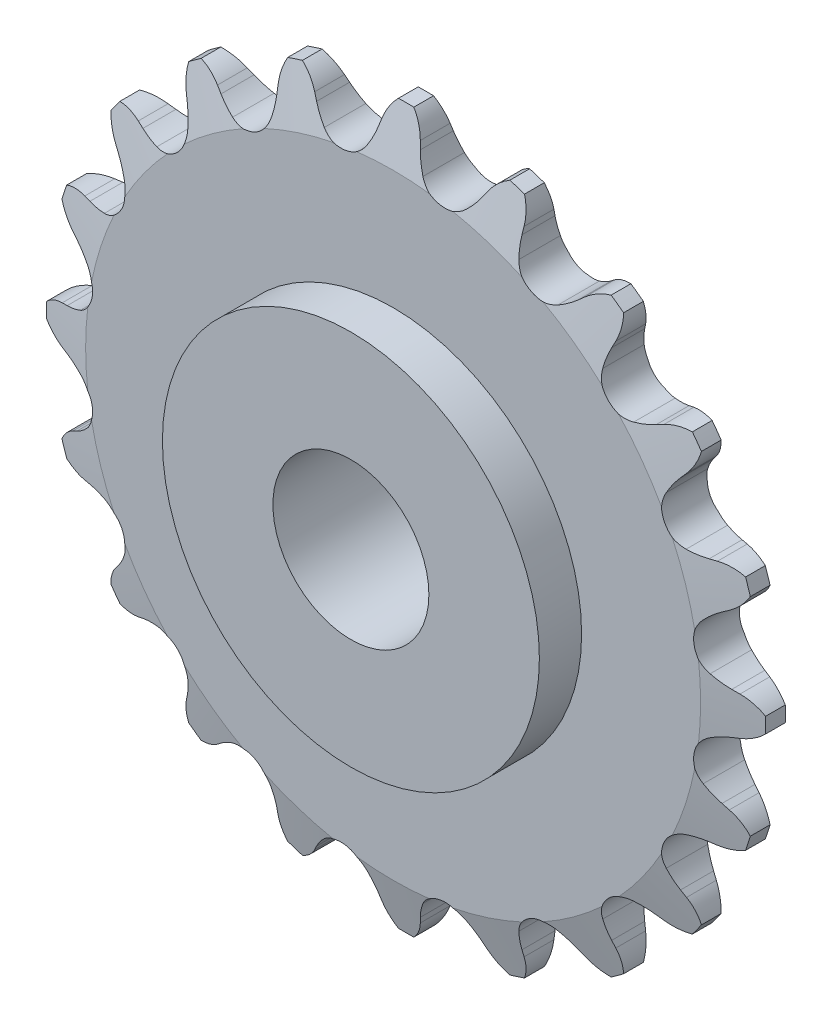
SolidWorks part; units mm, degrees
material "Plain Carbon Steel"
ref_plane "Front Plane" through (0, 0, 0) normal (0, 0, 1) x (1, 0, 0)
ref_plane "Top Plane" through (0, 0, 0) normal (0, 1, 0) x (1, 0, 0)
ref_plane "Right Plane" through (0, 0, 0) normal (1, 0, 0) x (0, 0, -1)
sketch "Sketch0" plane through (0, 0, 0) normal (0, 0, 1) x (1, 0, 0)
  line L0 (3.175, -20.0462) -> (0, 0) construction
  line L1 (0, 0) -> (9.2142, -18.0839) construction
  line L2 (0, 0) -> (-3.175, -20.0462) construction
  line L3 (3.175, -20.0462) -> (9.2142, -18.0839) construction
  line L4 (3.175, -20.0462) -> (-3.175, -20.0462) construction
  line L5 (5.2772, -20.0402) -> (5.0611, -19.6917)
  line L6 (3.175, -20.0462) -> (0, -20.549) construction
  line L7 (1.1739, -20.6901) -> (1.2717, -20.2918)
  line L8 (0, -20.0462) -> (0, -21.9512) construction
  line L9 (4.3326, -18.8048) -> (1.3734, -21.9781) construction
  line L10 (0, 0) -> (0, -20.0462) construction
  line L11 (5.0611, -19.6917) -> (1.3734, -21.9781) construction
  line L12 (0, -21.9512) -> (0, -22.3247) construction
  line L13 (7.5715, -18.6176) -> (5.2772, -20.0402) construction
  circle A0 centre (0, 0) radius 21.9512 construction
  circle A1 centre (0, 0) radius 20.296 construction
  arc A2 (-1.6423, -22.7387) -> (8.5885, -21.1183) centre (0, 0) ccw
  circle A3 centre (0, 0) radius 22.3247 construction
  circle A4 centre (3.175, -20.0462) radius 1.651 construction
  arc A7 (4.3326, -18.8048) -> (1.6905, -19.2233) centre (3.175, -20.0462) ccw
  circle A8 centre (3.175, -20.0462) radius 1.6974 construction
  arc A9 (5.2772, -20.0402) -> (8.5885, -21.1183) centre (7.5715, -18.6176) ccw
  arc A10 (5.0611, -19.6917) -> (4.3326, -18.8048) centre (1.3734, -21.9781) ccw
  arc A11 (1.1739, -20.6901) -> (-1.6423, -22.7387) centre (-1.4478, -20.0462) cw
  arc A12 (1.2717, -20.2918) -> (1.6905, -19.2233) centre (5.4854, -21.3268) cw
  dimension "D1" = 1.6974
  dimension "R" = 1.6974
sketch "Sketch1" plane through (0, 0, 0) normal (1, 0, 0) x (0, 0, -1)
  line L0 (-1.397, 0) -> (1.397, 0)
  line L1 (-1.397, 0) -> (-1.397, 18.7762)
  line L2 (-1.397, 18.7762) -> (-0.6032, 21.9512)
  line L3 (-0.6032, 21.9512) -> (0.6032, 21.9512)
  line L4 (0.6032, 21.9512) -> (1.397, 18.7762)
  line L5 (1.397, 18.7762) -> (1.397, 0)
  line L7 (0, 21.9512) -> (0, 0) construction
  line L8 (-1.397, 18.7762) -> (1.397, 18.7762) construction
  line L9 (0, 21.9512) -> (0, -21.9512) construction
  line L10 (-1.397, 18.7762) -> (-1.397, 21.9512) construction
  line L11 (-1.397, 21.9512) -> (-0.6032, 21.9512) construction
  line L12 (0.6032, 21.9512) -> (1.397, 21.9512) construction
  line L13 (1.397, 21.9512) -> (1.397, 18.7762) construction
revolve "Revolve1" add sketch "Sketch1" angle 360 mid plane about L0
extrude "Cut-Extrude1" cut sketch "Sketch0" against normal through all and the other way through all
pattern_circular "CirPattern1" count 20 over 360 about axis through (0, 0, 0) along (0, 0, 1) of "Cut-Extrude1"
sketch "Sketch2" plane through (0, 0, 0) normal (0, 0, 1) x (1, 0, 0)
  circle A0 centre (0, 0) radius 4.7625 construction
  circle A1 centre (0, 0) radius 11.5094
  circle A2 centre (0, 0) radius 21.971 construction
  dimension "Bore" = 9.525
  dimension "Hub Dia." = 23.0188
  dimension "OD" = 43.942
extrude "Boss-Extrude1" add sketch "Sketch2" along normal mid plane 7.9502
sketch "Sketch3" plane through (0, 0, 0) normal (0, 0, 1) x (1, 0, 0)
  circle A0 centre (0, 0) radius 4.7625 construction
  circle A1 centre (0, 0) radius 4.7625
extrude "Cut-Extrude2" cut sketch "Sketch3" along normal through all and the other way through all
equation "\"360/N@Sketch0\" = 360/\"Teeth@CirPattern1\""
equation "\"Ds@Sketch0\" = 1.005 * \"Dr@Sketch0\" + 0.003"
equation "\"R@Sketch0\" = 1/2 * \"Ds@Sketch0\""
equation "\"A@Sketch0\" = 35 +  ( 60 / \"Teeth@CirPattern1\" ) "
equation "\"B@Sketch0\" = 18 -  ( 56 / \"Teeth@CirPattern1\" )"
equation "\"ac@Sketch0\" = 0.8 * \"Dr@Sketch0\""
equation "\"ab@Sketch0\" = 1.4 * \"Dr@Sketch0\""
equation "\"J@Sketch0\" = 0.3 * \"Pitch@Sketch0\""
equation "\"h@Sketch1\" = \"Pitch@Sketch0\" / 2"
equation "\"g@Sketch1\" = \"h@Sketch1\" / 4"
